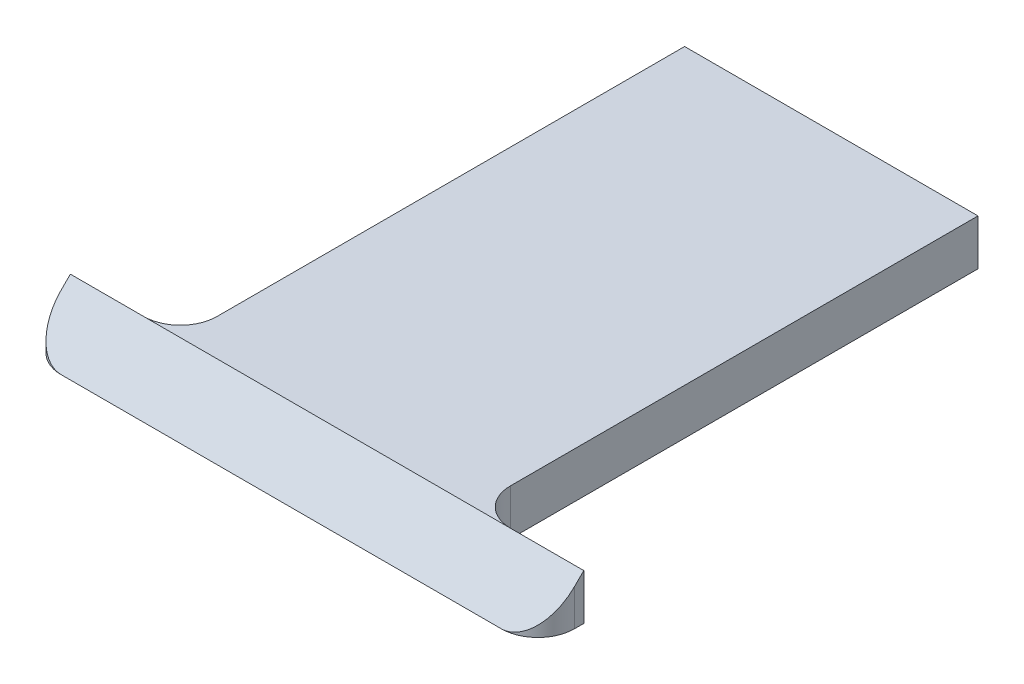
SolidWorks part; units mm, degrees
ref_plane "Front Plane" through (0, 0, 0) normal (0, 0, 1) x (1, 0, 0)
ref_plane "Top Plane" through (0, 0, 0) normal (0, 1, 0) x (1, 0, 0)
ref_plane "Right Plane" through (0, 0, 0) normal (1, 0, 0) x (0, 0, -1)
sketch "Sketch1" plane through (0, 0, 0) normal (0, 1, 0) x (1, 0, 0)
  line L0 (0, 0) -> (140, 0)
  line L1 (140, 0) -> (140, 12.5)
  line L2 (140, 12.5) -> (110, 12.5)
  line L3 (110, 12.5) -> (110, 150)
  line L4 (110, 150) -> (30, 150)
  line L5 (30, 150) -> (30, 12.5)
  line L6 (30, 12.5) -> (0, 12.5)
  line L7 (0, 12.5) -> (0, 0)
  dimension "D1" = 140
  dimension "D2" = 30
  dimension "D3" = 12.5
  dimension "D4" = 150
extrude "Boss-Extrude1" add sketch "Sketch1" along normal blind 12.5
fillet "Fillet1" radius 10 2 edges at (140, 6.25, 0) (0, 6.25, 0)
sketch "Sketch3" plane through (0, 0, 0) normal (1, 0, 0) x (0, 0, -1)
  line L0 (0, 0) -> (12.5, 12.5)
  line L1 (0, 0) -> (0, 12.5)
  line L2 (0, 12.5) -> (12.5, 12.5)
extrude "Cut-Extrude1" cut sketch "Sketch3" against normal through all both and the other way through all
fillet "Fillet5" radius 10 2 edges at (30, 6.25, -12.5) (110, 6.25, -12.5)
